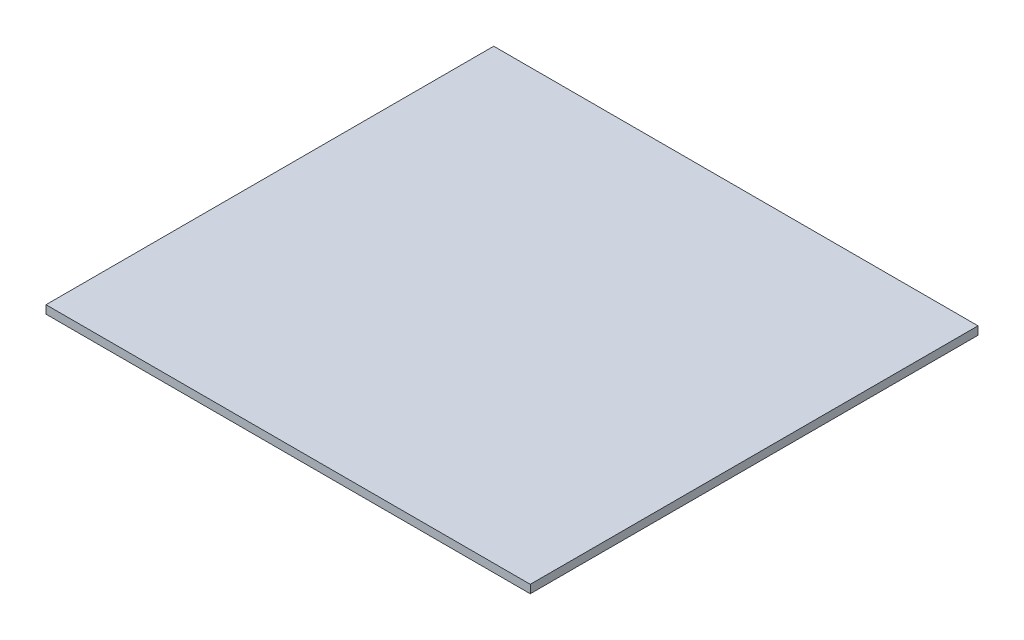
SolidWorks part; units mm, degrees
ref_plane "Alzado" through (0, 0, 0) normal (0, 0, 1) x (1, 0, 0)
ref_plane "Planta" through (0, 0, 0) normal (0, 1, 0) x (1, 0, 0)
ref_plane "Vista lateral" through (0, 0, 0) normal (1, 0, 0) x (0, 0, -1)
sketch "Croquis_repisa" plane through (0, 0, 0) normal (0, 1, 0) x (1, 0, 0)
  line L1 (-530, -490) -> (530, -490)
  line L2 (-530, -490) -> (-530, 490)
  line L3 (-530, 490) -> (530, 490)
  line L4 (530, -490) -> (530, 490)
  line L5 (-530, -490) -> (530, 490) construction
  line L6 (-530, 490) -> (530, -490) construction
  point P0 (0, 0)
  dimension "D1" = 530
  dimension "D2" = 490
extrude "Repisa_1060x980x18" add sketch "Croquis_repisa" along normal blind 18
